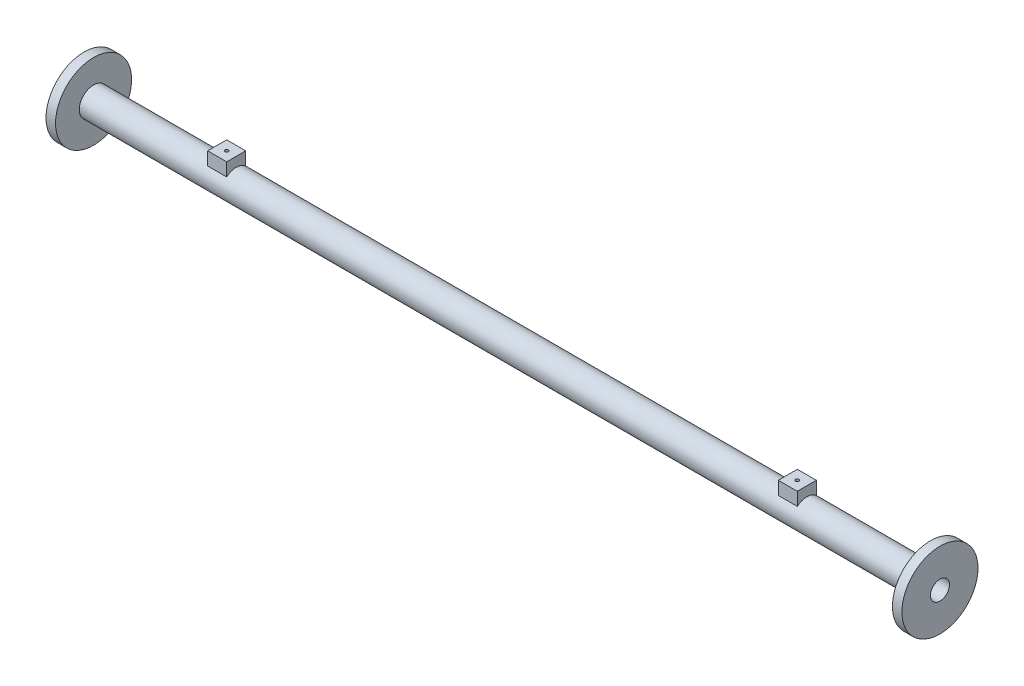
SolidWorks part; units mm, degrees
material "ABS PC"
ref_plane "Front Plane" through (0, 0, 0) normal (0, 0, 1) x (1, 0, 0)
ref_plane "Top Plane" through (0, 0, 0) normal (0, 1, 0) x (1, 0, 0)
ref_plane "Right Plane" through (0, 0, 0) normal (1, 0, 0) x (0, 0, -1)
sketch "Sketch1" plane through (0, 0, 0) normal (1, 0, 0) x (0, 0, -1)
  circle A0 centre (0, 0) radius 19.05
  circle A1 centre (0, 0) radius 12.7
  dimension "D1" = 25.4
  dimension "D2" = 38.1
extrude "Boss-Extrude1" add sketch "Sketch1" along normal mid plane 1143
sketch "Sketch2" plane through (571.5, 0, 0) normal (1, 0, 0) x (0, 0, -1)
  circle A0 centre (0, 0) radius 12.7 construction
  circle A1 centre (0, 0) radius 12.7
  circle A2 centre (0, 0) radius 50.8
  dimension "D1" = 101.6
extrude "Boss-Extrude2" add sketch "Sketch2" against normal blind 12.7
sketch "Sketch3" plane through (-571.5, 0, 0) normal (-1, 0, 0) x (0, 0, 1)
  circle A0 centre (0, 0) radius 50.8
  circle A1 centre (0, 0) radius 12.7 construction
  circle A2 centre (0, 0) radius 12.7
  dimension "D1" = 101.6
extrude "Boss-Extrude3" add sketch "Sketch3" against normal blind 12.7
sketch "Sketch4" plane through (0, 0, 0) normal (0, 1, 0) x (1, 0, 0)
  line L0 (0, 0) -> (0, 53.2725) construction
  line L1 (-393.7, -12.7) -> (-368.3, -12.7)
  line L2 (-393.7, -12.7) -> (-393.7, 12.7)
  line L3 (-393.7, 12.7) -> (-368.3, 12.7)
  line L4 (-368.3, -12.7) -> (-368.3, 12.7)
  line L5 (-393.7, -12.7) -> (-368.3, 12.7) construction
  line L6 (-393.7, 12.7) -> (-368.3, -12.7) construction
  line L7 (393.7, 12.7) -> (368.3, -12.7) construction
  line L8 (393.7, -12.7) -> (368.3, 12.7) construction
  line L9 (368.3, -12.7) -> (368.3, 12.7)
  line L10 (393.7, 12.7) -> (368.3, 12.7)
  line L11 (393.7, -12.7) -> (393.7, 12.7)
  line L12 (393.7, -12.7) -> (368.3, -12.7)
  circle A0 centre (-381, 0) radius 2.286
  circle A1 centre (381, 0) radius 2.286
  point P0 (-381, 0)
  dimension "D1" = 4.572
  dimension "D2" = 25.4
  dimension "D3" = 381
extrude "Boss-Extrude4" add sketch "Sketch4" against normal up to next from offset 31.75
